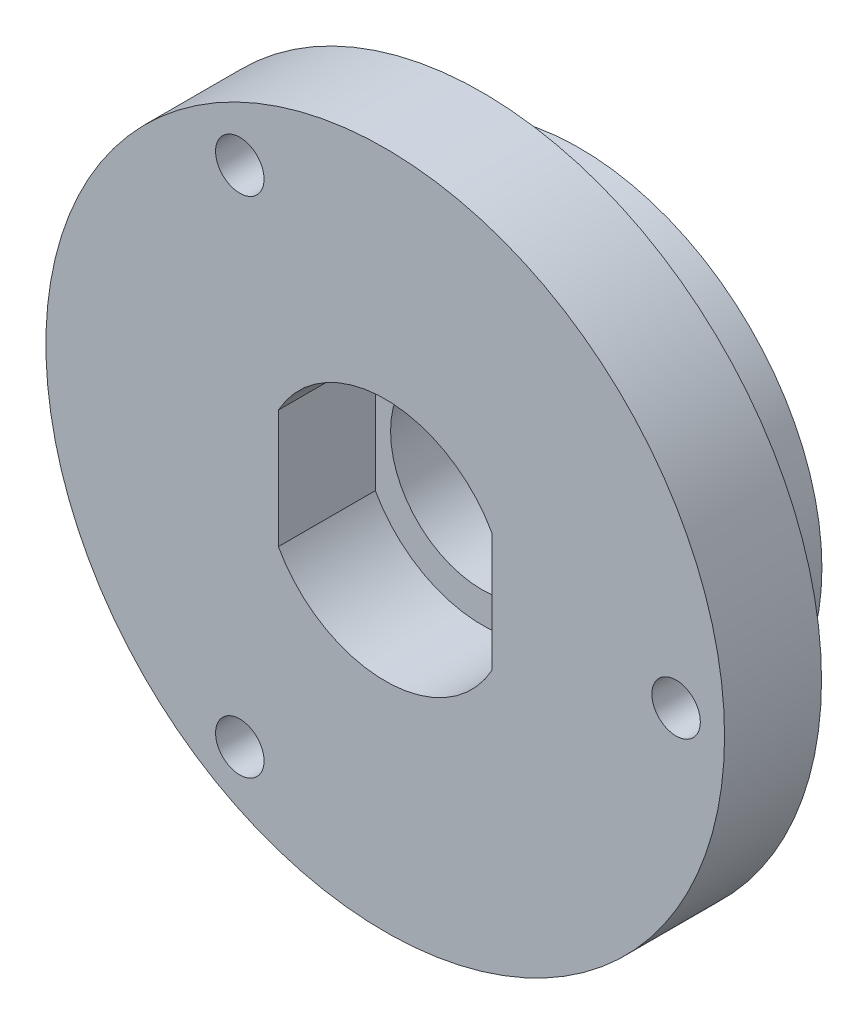
SolidWorks part; units mm, degrees
ref_plane "Front Plane" through (0, 0, 0) normal (0, 0, 1) x (1, 0, 0)
ref_plane "Top Plane" through (0, 0, 0) normal (0, 1, 0) x (1, 0, 0)
ref_plane "Right Plane" through (0, 0, 0) normal (1, 0, 0) x (0, 0, -1)
sketch "Sketch1" plane through (0, 0, 0) normal (0, 0, 1) x (1, 0, 0)
  circle A0 centre (0, 0) radius 7.9375
  dimension "D1" = 15.875
extrude "Boss-Extrude1" add sketch "Sketch1" along normal blind 3.188
sketch "Sketch2" plane through (0, 0, 3.188) normal (0, 0, 1) x (1, 0, 0)
  circle A0 centre (0, 0) radius 11.1125
  dimension "D1" = 22.225
extrude "Boss-Extrude2" add sketch "Sketch2" along normal blind 3.175
sketch "Sketch3" plane through (0, 0, 6.363) normal (0, 0, 1) x (1, 0, 0)
  line L0 (3.5, 1.9365) -> (3.5, -1.9365)
  line L1 (-3.5, -1.9365) -> (-3.5, 1.9365)
  circle A0 centre (0, 0) radius 4
  dimension "D1" = 3.873
  dimension "D2" = 8
  dimension "D3" = 3.873
extrude "Cut-Extrude2" cut sketch "Sketch3" along direction (0, 0, 1) on the side against the normal up to surface (3.175 mm away) contours L0 A0 L1
sketch "Sketch4" plane through (0, 0, 0) normal (0, 0, -1) x (-1, 0, 0)
  circle A0 centre (0, 0) radius 3
  dimension "D1" = 6
extrude "Cut-Extrude3" cut sketch "Sketch4" against normal up to next
sketch "Sketch5" plane through (0, 0, 6.363) normal (0, 0, 1) x (1, 0, 0)
  circle A0 centre (0, 0) radius 9.525
  circle A1 centre (-4.7625, 8.2489) radius 0.7938
  circle A2 centre (-4.7625, -8.2489) radius 0.7938
  circle A4 centre (9.525, 0) radius 0.7937
  point P3 (0, 9.525)
  point P4 (9.525, 0)
  point P5 (0, -9.525)
  point P6 (-9.525, 0)
  dimension "D1" = 19.05
  dimension "D2" = 1.5875
  dimension "D3" = 120
  dimension "D4" = 120
extrude "Cut-Extrude5" cut sketch "Sketch5" against normal up to next contours A0 A1 | A0 A1 | A0 A4 | A0 A4 | A0 A2 | A0 A2
